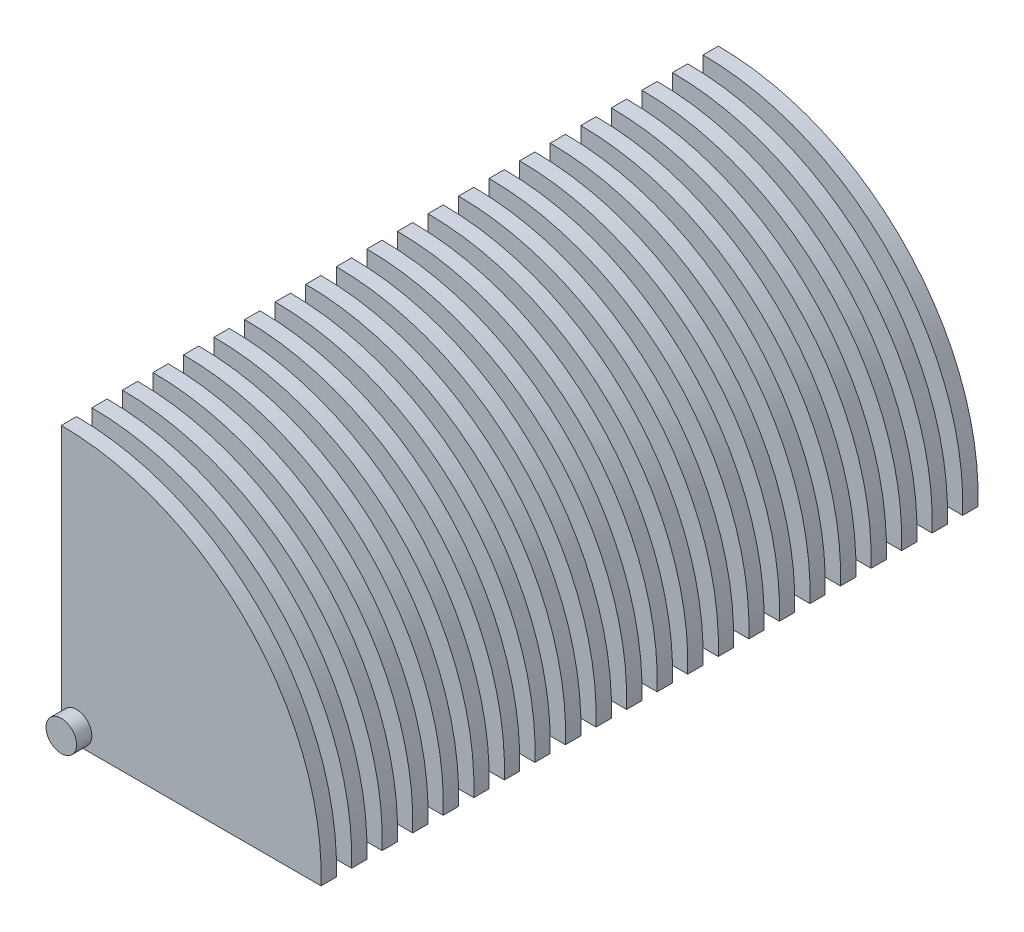
SolidWorks part; units mm, degrees
ref_plane "Front Plane" through (0, 0, 0) normal (0, 0, 1) x (1, 0, 0)
ref_plane "Top Plane" through (0, 0, 0) normal (0, 1, 0) x (1, 0, 0)
ref_plane "Right Plane" through (0, 0, 0) normal (1, 0, 0) x (0, 0, -1)
sketch "Sketch1" plane through (0, 0, 0) normal (0, 0, 1) x (1, 0, 0)
  line L2 (85, 0) -> (0, 0)
  line L3 (0, 0) -> (0, 88)
  arc A1 (0, 88) -> (85, 0) centre (0, 2.9489) cw
  dimension "D1" = 88
  dimension "D2" = 85
extrude "Boss-Extrude1" add sketch "Sketch1" along normal blind 5
pattern_linear "LPattern1" count 22 spacing 10 along (0, 0, -1) of "Boss-Extrude1"
sketch "Sketch5" plane through (0, 0, -210) normal (0, 0, -1) x (-1, 0, 0)
  line L0 (0, 53.9) -> (0, -53.9) construction
  line L1 (48.4, 0) -> (-48.4, 0) construction
  circle A0 centre (-5, 5) radius 5
  dimension "D1" = 5
  dimension "D2" = 5
extrude "Boss-Extrude9" add sketch "Sketch5" along normal blind 10 and the other way blind 220 separate body contours A0
